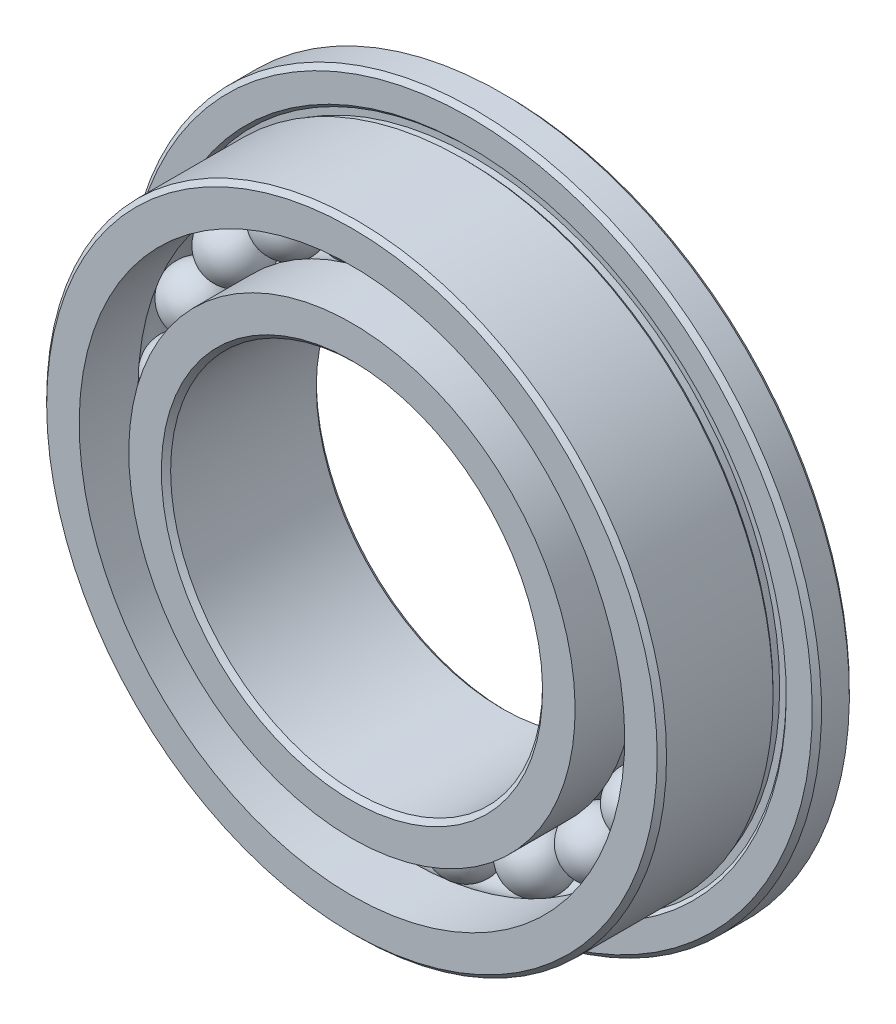
SolidWorks part; units mm, degrees
ref_plane "Front Plane" through (0, 0, 0) normal (0, 0, 1) x (1, 0, 0)
ref_plane "Top Plane" through (0, 0, 0) normal (0, 1, 0) x (1, 0, 0)
ref_plane "Right Plane" through (0, 0, 0) normal (1, 0, 0) x (0, 0, -1)
sketch "Sketch1" plane through (0, 0, 0) normal (1, 0, 0) x (0, 0, -1)
  line L0 (0, 5) -> (0, -5) construction
  line L1 (-1.25, 5) -> (1.25, 5) construction
  line L2 (0, 0) -> (1.25, 0) construction
  line L3 (1.25, 5.6) -> (1.25, -5.6) construction
  line L4 (1.25, -5.6) -> (0.65, -5.6) construction
  line L5 (1.25, 3) -> (0, 3) construction
  line L6 (1.25, 3) -> (1.25, -3) construction
  dimension "OD" = 10
  dimension "Width" = 2.5
  dimension "Flange Thickness" = 0.6
  dimension "ID" = 6
  dimension "Flange OD" = 11.2
sketch "Sketch2" plane through (0, 0, 0) normal (1, 0, 0) x (0, 0, -1)
  line L0 (1.25, 5.6) -> (0.65, 5.6)
  line L1 (0.65, 5.6) -> (0.65, 5.1061)
  line L2 (0.5439, 5) -> (-1.25, 5)
  line L3 (-1.25, 5) -> (-1.25, 4.4)
  line L4 (-1.25, 4.4) -> (-0.3, 4.4)
  line L5 (1.25, 5.6) -> (1.25, -5.6) construction
  line L6 (1.25, 4.4) -> (1.25, 5.6)
  line L7 (1.25, 3) -> (-1.25, 3)
  line L8 (-1.25, 3) -> (-1.25, 3.6)
  line L9 (-1.25, 3.6) -> (-0.3, 3.6)
  line L10 (1.25, 3.6) -> (1.25, 3)
  line L11 (0, 5) -> (0, 3) construction
  line L12 (-0.5, 4) -> (0.5, 4) construction
  line L13 (0.3, 4.4) -> (1.25, 4.4)
  line L14 (0.3, 3.6) -> (1.25, 3.6)
  line L15 (0.65, 5.1061) -> (0.703, 5.053)
  line L16 (0.703, 5.053) -> (0.703, 4.947)
  line L17 (0.703, 4.947) -> (0.597, 4.947)
  line L18 (0.597, 4.947) -> (0.5439, 5)
  line L19 (0.65, 5) -> (0.703, 4.947) construction
  line L20 (0.703, 5.053) -> (0.597, 4.947) construction
  line L21 (0.5439, 5) -> (0.65, 5) construction
  line L22 (0.65, 5) -> (0.65, 5.1061) construction
  circle A0 centre (0, 4) radius 0.5 construction
  arc A1 (-0.3, 4.4) -> (0.3, 4.4) centre (0, 4) cw
  arc A2 (-0.3, 3.6) -> (0.3, 3.6) centre (0, 4) ccw
  dimension "D1" = 2
  dimension "Ball Dia." = 1
  dimension "D2" = 135
  dimension "D3" = 0.15
  dimension "D4" = 0.8
  dimension "Race Thikness" = 0.6
revolve "Revolve1" add sketch "Sketch2" angle 360 about L2
fillet "Fillet1" radius 0.075 3 edges at (0, -5.6, -1.25) (0, -5.6, -0.65) (0, -5, 1.25) profile chamfer
sketch "Sketch3" plane through (0, 0, 0) normal (0, 0, 1) x (1, 0, 0)
  line L0 (-3, 0) -> (3, 0) construction
  line L1 (-5, 0) -> (5, 0) construction
  point P5 (0, 0)
  dimension "ID2" = 6
  dimension "OD2" = 10
fillet "Fillet2" radius 0.075 2 edges at (0, -3, -1.25) (0, -3, 1.25) profile chamfer
sketch "Sketch7" plane through (0, 0, 0) normal (0, 0, 1) x (1, 0, 0)
  line L0 (0, 4.5) -> (0, 3.5)
  line L1 (0, 5.6) -> (0, -5.6) construction
  line L2 (-0.5669, 4.5) -> (0, 0) construction
  line L3 (0, 0) -> (0.5669, 4.5) construction
  line L4 (0.5669, 4.5) -> (-0.5669, 4.5) construction
  circle A0 centre (0, 4) radius 0.5 construction
  circle A1 centre (0, 0) radius 4.5 construction
  circle A2 centre (0, 0) radius 3.5 construction
  arc A4 (0, 4.5) -> (0, 3.5) centre (0, 4) ccw
  dimension "D1" = 14.362
revolve "Revolve3" add sketch "Sketch7" angle 360 about L0
pattern_circular "CirPattern3" count 21 over 360 about axis through (0, 0, 0) along (0, 0, 1) of bodies 107
sketch "Sketch8" plane through (0, 0, 0) normal (1, 0, 0) x (0, 0, -1)
  line L0 (-1.25, 5) -> (1.25, 5) construction
  line L1 (1.25, 5) -> (1.25, 5.6) construction
  line L2 (-1.25, -5) -> (1.25, -5) construction
  line L3 (1.25, 5.6) -> (1.25, -5.6) construction
  dimension "D1" = 10
equation "\"Ball Dia.@Sketch2\" = ( \"OD@Sketch1\" - \"ID@Sketch1\" ) * .25"
equation "\"D3@Sketch2\"=\"Flange Thickness@Sketch1\"/4"
equation "\"D1@Fillet1\" = \"Race Thikness@Sketch2\" / 8"
equation "\"ID2@Sketch3\" = \"ID@Sketch1\""
equation "\"OD2@Sketch3\" = \"OD@Sketch1\""
equation "\"D1@Fillet2\" = \"Race Thikness@Sketch2\" / 8"
equation "\"D1@CirPattern3\"=360/\"D1@Sketch7\"-4"
equation "\"D4@Sketch2\" = ( \"OD@Sketch1\" - \"ID@Sketch1\" ) * .2"
